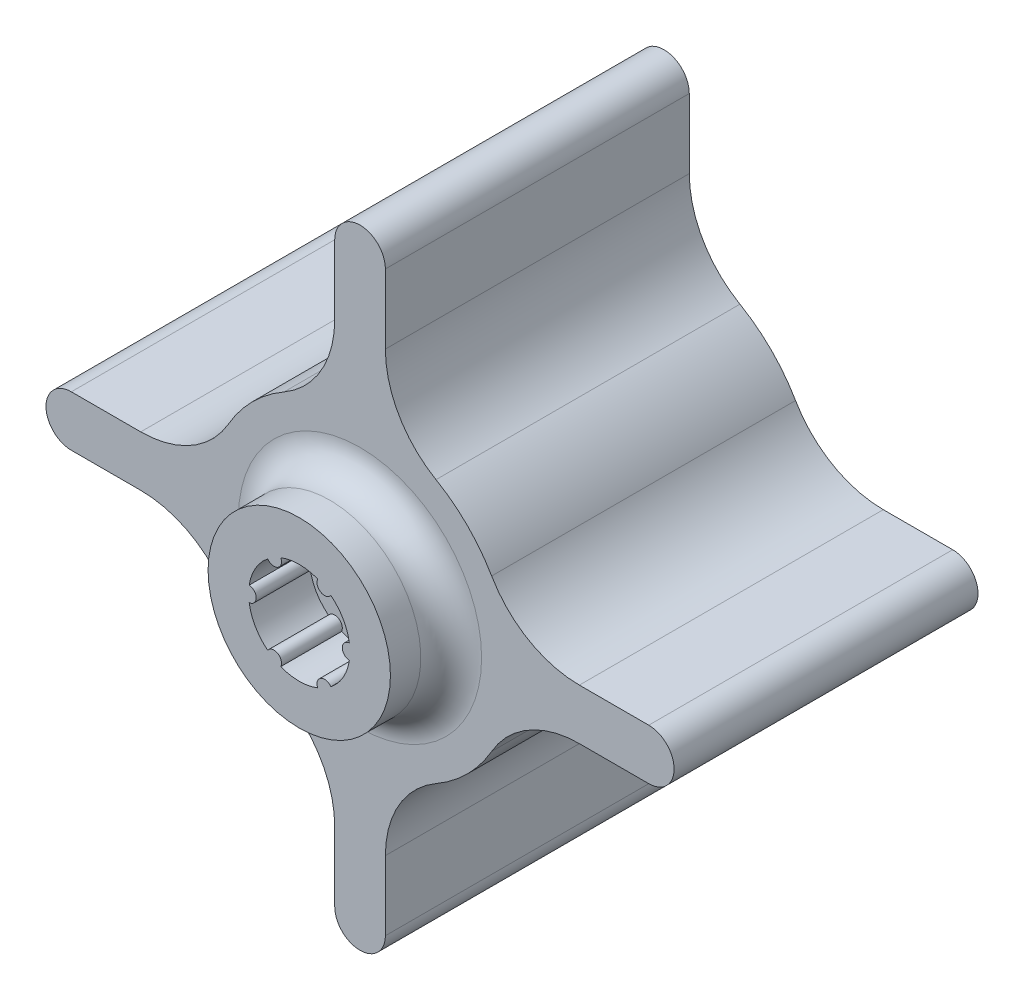
SolidWorks part; units mm, degrees
material "PP Copolymer"
ref_plane "Alzado" through (0, 0, 0) normal (0, 0, 1) x (1, 0, 0)
ref_plane "Planta" through (0, 0, 0) normal (0, 1, 0) x (1, 0, 0)
ref_plane "Vista lateral" through (0, 0, 0) normal (1, 0, 0) x (0, 0, -1)
sketch "Croquis2" plane through (0, 0, 0) normal (0, 0, 1) x (1, 0, 0)
  circle A0 centre (0, 0) radius 4.5
  arc A1 (2.4719, 0.3739) -> (1.5598, 1.9537) centre (0, 0) ccw
  arc A2 (2.4719, 0.3739) -> (2.4719, -0.3739) centre (2.5, 0) ccw
  arc A3 (1.5598, -1.9537) -> (0.9121, -2.3277) centre (1.25, -2.1651) ccw
  arc A4 (-0.9121, -2.3277) -> (-1.5598, -1.9537) centre (-1.25, -2.1651) ccw
  arc A5 (-2.4719, -0.3739) -> (-2.4719, 0.3739) centre (-2.5, 0) ccw
  arc A6 (-1.5598, 1.9537) -> (-0.9121, 2.3277) centre (-1.25, 2.1651) ccw
  arc A7 (0.9121, 2.3277) -> (1.5598, 1.9537) centre (1.25, 2.1651) ccw
  arc A8 (-0.9121, -2.3277) -> (0.9121, -2.3277) centre (0, 0) ccw
  arc A9 (-2.4719, -0.3739) -> (-1.5598, -1.9537) centre (0, 0) ccw
  arc A10 (-1.5598, 1.9537) -> (-2.4719, 0.3739) centre (0, 0) ccw
  arc A11 (0.9121, 2.3277) -> (-0.9121, 2.3277) centre (0, 0) ccw
  arc A12 (1.5598, -1.9537) -> (2.4719, -0.3739) centre (0, 0) ccw
  dimension "D1" = 9
  dimension "D2" = 5
  dimension "D3" = 0.75
  dimension "D4" = 6
extrude "Saliente-Extruir1" add sketch "Croquis2" along normal blind 3
sketch "Croquis3" plane through (0, 0, 0) normal (0, 0, -1) x (-1, 0, 0)
  line L0 (1.25, 10.8253) -> (1.25, 14.25)
  line L2 (-1.25, 14.25) -> (-1.25, 10.8253)
  line L3 (0, 15.5) -> (0, 0) construction
  line L4 (10.8253, -1.25) -> (14.25, -1.25)
  line L5 (14.25, 1.25) -> (10.8253, 1.25)
  line L6 (-1.25, -10.8253) -> (-1.25, -14.25)
  line L7 (1.25, -14.25) -> (1.25, -10.8253)
  line L8 (-10.8253, 1.25) -> (-14.25, 1.25)
  line L9 (-14.25, -1.25) -> (-10.8253, -1.25)
  circle A1 centre (0, 0) radius 1.25
  arc A2 (-6.4952, -3.75) -> (-3.75, -6.4952) centre (0, 0) ccw
  arc A4 (1.25, 14.25) -> (-1.25, 14.25) centre (0, 14.25) ccw
  arc A5 (14.25, -1.25) -> (14.25, 1.25) centre (14.25, 0) ccw
  arc A6 (-1.25, -14.25) -> (1.25, -14.25) centre (0, -14.25) ccw
  arc A7 (-14.25, 1.25) -> (-14.25, -1.25) centre (-14.25, 0) ccw
  arc A11 (6.4952, 3.75) -> (3.75, 6.4952) centre (0, 0) ccw
  arc A12 (-3.75, 6.4952) -> (-6.4952, 3.75) centre (0, 0) ccw
  arc A13 (3.75, -6.4952) -> (6.4952, -3.75) centre (0, 0) ccw
  arc A14 (6.4952, -3.75) -> (10.8253, -1.25) centre (10.8253, -6.25) cw
  arc A15 (1.25, -10.8253) -> (3.75, -6.4952) centre (6.25, -10.8253) cw
  arc A16 (-1.25, -10.8253) -> (-3.75, -6.4952) centre (-6.25, -10.8253) ccw
  arc A17 (-10.8253, -1.25) -> (-6.4952, -3.75) centre (-10.8253, -6.25) cw
  arc A18 (-10.8253, 1.25) -> (-6.4952, 3.75) centre (-10.8253, 6.25) ccw
  arc A19 (-1.25, 10.8253) -> (-3.75, 6.4952) centre (-6.25, 10.8253) cw
  arc A20 (1.25, 10.8253) -> (3.75, 6.4952) centre (6.25, 10.8253) ccw
  arc A21 (6.4952, 3.75) -> (10.8253, 1.25) centre (10.8253, 6.25) ccw
  point P32 (1.25, -7.3951)
  point P35 (-1.25, -7.3951)
  point P38 (-7.3951, -1.25)
  point P43 (-1.25, 7.3951)
  dimension "D1" = 2.5
  dimension "D2" = 15.5
  dimension "D4" = 4
  dimension "D5" = 15
  dimension "D6" = 5
  dimension "D3" = 2.5
extrude "Saliente-Extruir2" add sketch "Croquis3" along normal blind 15
fillet "Redondeo1" radius 1.5 1 edges at (4.5, 0, 0)
